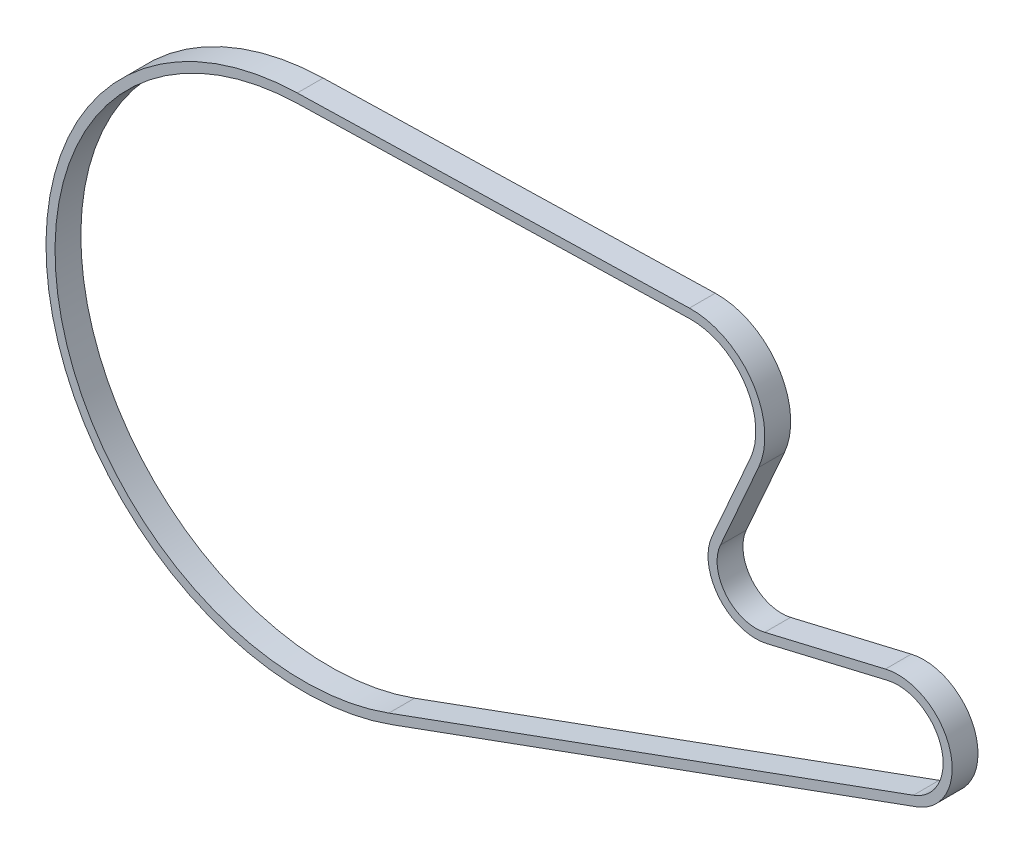
SolidWorks part; units mm, degrees
ref_plane "Plano frontal" through (0, 0, 0) normal (0, 0, 1) x (1, 0, 0)
ref_plane "Plano superior" through (0, 0, 0) normal (0, 1, 0) x (1, 0, 0)
ref_plane "Plano direito" through (0, 0, 0) normal (1, 0, 0) x (0, 0, -1)
sketch "Esboço1" plane through (0, 0, 0) normal (0, 0, 1) x (1, 0, 0)
  line L0 (0, 0) -> (46, 0) construction
  line L17 (0, 0) -> (-19.25, 0) construction
  line L18 (46, 0) -> (50.2, 0) construction
  line L34 (45.1953, 3.4062) -> (35.8525, 1.1991)
  line L38 (34.5728, 12.9777) -> (31.618, 6.2965)
  line L39 (29.8758, 19.9985) -> (-0.4783, 19.2441)
  line L45 (6.591, -18.0865) -> (47.1984, -3.2885)
  line L46 (6.8307, -18.7442) -> (47.438, -3.9461)
  line L47 (45.0344, 4.0875) -> (35.6915, 1.8804)
  line L48 (35.2129, 12.6945) -> (32.2582, 6.0134)
  line L49 (29.8584, 20.6982) -> (-0.4957, 19.9438)
  arc A25 (47.1984, -3.2885) -> (45.1953, 3.4062) centre (46, 0) ccw
  arc A31 (-0.4783, 19.2441) -> (6.591, -18.0865) centre (0, 0) ccw
  arc A40 (31.618, 6.2965) -> (35.8525, 1.1991) centre (35.0018, 4.8) ccw
  arc A42 (34.5728, 12.9777) -> (29.8758, 19.9985) centre (30, 15) ccw
  arc A48 (-0.4957, 19.9438) -> (6.8307, -18.7442) centre (0, 0) ccw
  arc A49 (47.438, -3.9461) -> (45.0344, 4.0875) centre (46, 0) ccw
  arc A50 (32.2582, 6.0134) -> (35.6915, 1.8804) centre (35.0018, 4.8) ccw
  arc A51 (35.2129, 12.6945) -> (29.8584, 20.6982) centre (30, 15) ccw
  dimension "D1" = 7.4
  dimension "D2" = 0.7
  dimension "D4" = 4.8
  dimension "D5" = 46
  dimension "D6" = 3.5
  dimension "D7" = 186.0684
  dimension "D8" = 0
  dimension "D3" = 38.5
  dimension "D9" = 12
  dimension "D12" = 10
  dimension "D14" = 16
  dimension "D15" = 15
extrude "Ressalto-extrusão1" add sketch "Esboço1" along normal blind 2
